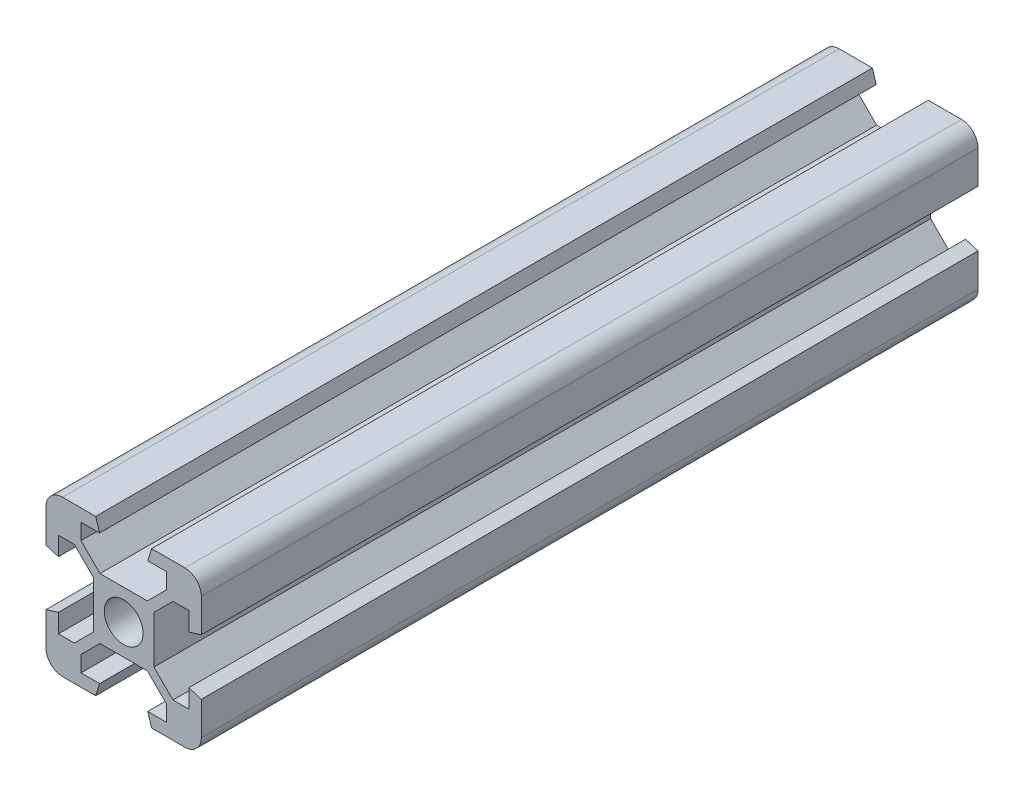
SolidWorks part; units mm, degrees
ref_plane "前视基准面" through (0, 0, 0) normal (0, 0, 1) x (1, 0, 0)
ref_plane "上视基准面" through (0, 0, 0) normal (0, 1, 0) x (1, 0, 0)
ref_plane "右视基准面" through (0, 0, 0) normal (1, 0, 0) x (0, 0, -1)
sketch "草图1" plane through (0, 0, 0) normal (0, 0, 1) x (1, 0, 0)
  line L0 (-10, 7.8787) -> (-10, 3.6)
  line L1 (-10, -10) -> (10, -10) construction
  line L2 (-10, -10) -> (-10, 7.8787) construction
  line L3 (-7.8787, 10) -> (10, 10) construction
  line L4 (10, -10) -> (10, 10) construction
  line L5 (-10, -10) -> (10, 10) construction
  line L6 (-10, 10) -> (10, -10) construction
  line L7 (-7.8787, 10) -> (-6.3596, 10)
  line L8 (-8.4, 5.5) -> (-8.4, 3.1)
  line L9 (10, 10) -> (3.6, 10)
  line L10 (-8.4, 5.5) -> (-6.3485, 5.5)
  line L11 (-6.3485, 5.5) -> (-3.9, 3.0515)
  line L12 (-10, 3.6) -> (-8.4, 3.1)
  line L13 (-5.5, 6.3485) -> (-3.0515, 3.9)
  line L14 (-5.5, 8.4) -> (-5.5, 6.3485)
  line L15 (-5.5, 8.4) -> (-3.1, 8.4)
  line L16 (-3.6, 10) -> (-3.1, 8.4)
  line L17 (-7.8787, 10) -> (-3.6, 10)
  line L18 (-3.9, 3.0515) -> (-3.9, -3.0515)
  line L19 (-1.5553, 0) -> (1.4012, 0) construction
  line L20 (0, 1.9142) -> (0, -2.5) construction
  line L21 (3.6, 10) -> (3.1, 8.4)
  line L22 (5.5, 8.4) -> (3.1, 8.4)
  line L23 (5.5, 8.4) -> (5.5, 6.3485)
  line L24 (5.5, 6.3485) -> (3.0515, 3.9)
  line L25 (10, 3.6) -> (8.4, 3.1)
  line L26 (6.3485, 5.5) -> (3.9, 3.0515)
  line L27 (8.4, 5.5) -> (6.3485, 5.5)
  line L28 (8.4, 5.5) -> (8.4, 3.1)
  line L29 (10, 10) -> (6.3596, 10)
  line L30 (10, 10) -> (10, 3.6)
  line L31 (10, -10) -> (10, -3.6)
  line L32 (10, -3.6) -> (8.4, -3.1)
  line L33 (8.4, -5.5) -> (8.4, -3.1)
  line L34 (8.4, -5.5) -> (6.3485, -5.5)
  line L35 (6.3485, -5.5) -> (3.9, -3.0515)
  line L36 (5.5, -6.3485) -> (3.0515, -3.9)
  line L37 (5.5, -8.4) -> (5.5, -6.3485)
  line L38 (5.5, -8.4) -> (3.1, -8.4)
  line L39 (3.6, -10) -> (3.1, -8.4)
  line L40 (10, -10) -> (3.6, -10)
  line L41 (-5.5, -8.4) -> (-3.1, -8.4)
  line L42 (-5.5, -8.4) -> (-5.5, -6.3485)
  line L43 (-5.5, -6.3485) -> (-3.0515, -3.9)
  line L44 (-6.3485, -5.5) -> (-3.9, -3.0515)
  line L45 (-8.4, -5.5) -> (-6.3485, -5.5)
  line L46 (-8.4, -5.5) -> (-8.4, -3.1)
  line L47 (-10, -3.6) -> (-8.4, -3.1)
  line L48 (-3.6, -10) -> (-3.1, -8.4)
  line L49 (-10, -10) -> (-3.6, -10)
  line L50 (-10, -10) -> (-10, -3.6)
  line L51 (-3.0515, -3.9) -> (3.0515, -3.9)
  line L52 (3.9, -3.0515) -> (3.9, 3.0515)
  line L53 (-3.0515, 3.9) -> (3.0515, 3.9)
  line L54 (10, 10) -> (10, 3.6)
  line L57 (-10, -7.8787) -> (-7.8787, -10) construction
  circle A0 centre (0, 0) radius 2.5
  arc A1 (-10, 7.8787) -> (-7.8787, 10) centre (-7.8787, 7.8787) cw
  arc A2 (7.8787, 10) -> (10, 7.8787) centre (7.8787, 7.8787) cw
  arc A4 (10, -7.8787) -> (7.8787, -10) centre (7.8787, -7.8787) cw
  arc A5 (-7.8787, -10) -> (-10, -7.8787) centre (-7.8787, -7.8787) cw
  point P0 (0, 0)
  point P35 (-7.3743, 5.5)
  point P52 (-7.3743, -5.5)
  dimension "D9" = 5
  dimension "D1" = 20
  dimension "D2" = 20
  dimension "D3" = 6.4
  dimension "D4" = 6.9
  dimension "D5" = 1.6
  dimension "D6" = 0.6
  dimension "D7" = 4.5
  dimension "D8" = 6.1
  dimension "D10" = 1.5
extrude "凸台-拉伸1" add sketch "草图1" against normal blind 100 contours A5 L49 L48 L41 L42 L43 L51 L36 L37 L38 L39 L40 A4 L31 L32 L33 L34 L35 L52 L26 L27 L28 L25 L54 A2 L29 L9 L21 L22 L23 L24 L53 L13 L14 L15 L16 L17 L7 A1 L0 L12 L8 L10 L11 L18 L44 L45 L46 L47 L50
